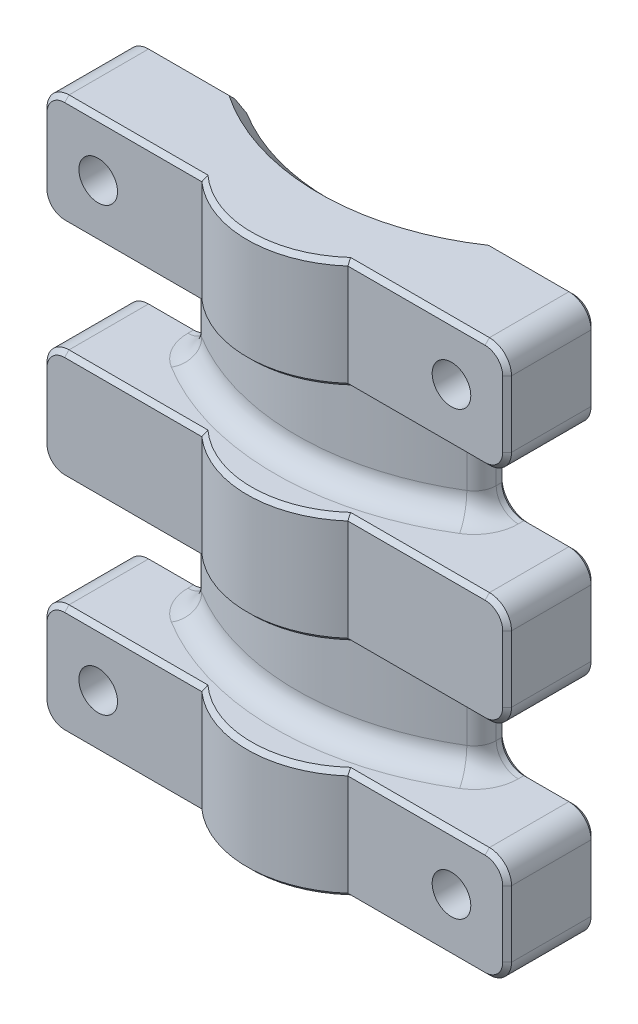
SolidWorks part; units mm, degrees
ref_plane "Front Plane" through (0, 0, 0) normal (0, 0, 1) x (1, 0, 0)
ref_plane "Top Plane" through (0, 0, 0) normal (0, 1, 0) x (1, 0, 0)
ref_plane "Right Plane" through (0, 0, 0) normal (1, 0, 0) x (0, 0, -1)
sketch "Sketch1" plane through (0, 0, 0) normal (0, 1, 0) x (1, 0, 0)
  line L0 (-21.0405, 41) -> (21.0405, 41) construction
  line L1 (-21.0405, 41) -> (21.0405, 41) construction
  line L2 (-21.0405, 26) -> (-6.6144, 26) construction
  line L3 (6.6144, 26) -> (21.0405, 26) construction
  line L4 (-6.6144, 26) -> (0, 26) construction
  line L5 (0, 26) -> (6.6144, 26) construction
  line L6 (0, 28.5) -> (0, 23.5) construction
  line L7 (0, 41) -> (0, 38) construction
  line L8 (-21.0405, 41) -> (-10.5357, 41)
  line L9 (10.5357, 41) -> (21.0405, 41)
  line L10 (-21.0405, 41) -> (-21.0405, 33)
  line L11 (-21.0405, 33) -> (-6.6144, 33)
  line L12 (21.0405, 33) -> (21.0405, 41)
  line L13 (6.6144, 33) -> (21.0405, 33)
  line L14 (0, 35) -> (0, 38) construction
  line L15 (-6.6144, 33) -> (-5.8828, 35.7651) construction
  arc A0 (-21.0405, 26) -> (-21.0405, 41) centre (-2.5, 33.5) cw construction
  arc A1 (21.0405, 41) -> (21.0405, 26) centre (2.5, 33.5) cw construction
  arc A2 (21.0405, 26) -> (21.0405, 41) centre (2.5, 33.5) ccw construction
  arc A3 (-6.6144, 26) -> (6.6144, 26) centre (0, 18.5) cw construction
  arc A4 (-6.6144, 26) -> (6.6144, 26) centre (0, 33.5) ccw construction
  arc A5 (-10.5357, 41) -> (10.5357, 41) centre (0, 58) ccw
  arc A6 (-6.6144, 33) -> (6.6144, 33) centre (0, 40.5) ccw
  arc A7 (-15.4919, 41) -> (15.4919, 41) centre (0, 58) ccw construction
  dimension "D1" = 20
  dimension "D2" = 3
  dimension "D3" = 8
  dimension "D4" = 3
extrude "Boss-Extrude1" add sketch "Sketch1" against normal up to surface (50 mm away) from surface at 25
sketch "Sketch2" plane through (0, 0, -41) normal (0, 0, -1) x (-1, 0, 0)
  line L0 (-16, 20) -> (16, 20) construction
  line L1 (0, 20) -> (0, -20) construction
  line L2 (-16, -20) -> (16, -20) construction
  circle A0 centre (-16, 20) radius 1.75
  circle A1 centre (16, 20) radius 1.75
  circle A2 centre (-16, -20) radius 1.75
  circle A3 centre (16, -20) radius 1.75
  point P15 (0, 0)
  dimension "D1" = 3.5
  dimension "D2" = 40
  dimension "D3" = 32
extrude "Cut-Extrude1" cut sketch "Sketch2" against normal through all
sketch "Sketch3" plane through (0, 0, 0) normal (0, 1, 0) x (1, 0, 0)
  line L1 (-21.0405, 41) -> (-21.0405, 8.3823)
  line L2 (-21.0405, 8.3823) -> (21.0405, 8.3823)
  line L3 (21.0405, 8.3823) -> (21.0405, 41)
  line L5 (0, 0) -> (0, 58) construction
  line L7 (-12.9615, 39) -> (-12.9615, 41)
  line L8 (-21.0405, 41) -> (-10.5357, 41) construction
  line L9 (12.9615, 39) -> (12.9615, 41)
  line L10 (10.5357, 41) -> (21.0405, 41) construction
  line L11 (-12.9615, 41) -> (-21.0405, 41)
  line L12 (12.9615, 41) -> (21.0405, 41)
  line L13 (-21.0405, 41) -> (-21.0405, 33) construction
  arc A0 (-12.9615, 39) -> (12.9615, 39) centre (0, 58) ccw
  arc A1 (-10.5357, 41) -> (10.5357, 41) centre (0, 58) ccw construction
  arc A2 (-15.4919, 41) -> (15.4919, 41) centre (0, 58) ccw construction
  arc A3 (-21.0405, 41) -> (-21.0405, 26) centre (-2.5, 33.5) ccw construction
  point P1 (-21.0405, 41)
  point P29 (21.0997, 40.852)
  dimension "D1" = 2
extrude "Cut-Extrude2" cut sketch "Sketch3" against normal blind 10 from offset 5 offset against normal yes
mirror "Mirror1" about plane through (0, 0, 0) normal (0, 1, 0) of "Cut-Extrude2"
chamfer "Chamfer1" distance 2 angle 45 4 edges at (-17.75, 20, -41) (14.25, 20, -41) (14.25, -20, -41) (-17.75, -20, -41)
chamfer "Chamfer2" distance 1 angle 45 2 edges at (0, -25, -38) (0, 25, -38)
fillet "Fillet1" radius 2 12 edges at (-21.0405, 15, -37) (-21.0405, 5, -37) (-21.0405, -5, -37) (-21.0405, -15, -37) (-21.0405, -25, -37) (21.0405, -25, -37) (21.0405, -15, -37) (21.0405, -5, -37) (21.0405, 5, -37) (21.0405, 15, -37) (21.0405, 25, -37) (-21.0405, 25, -37)
fillet "Fillet3" radius 2 4 edges at (12.9615, 10, -39) (12.9615, -10, -39) (-12.9615, -10, -39) (-12.9615, 10, -39)
chamfer "Chamfer3" [suppressed] distance 1 angle 45
chamfer "Chamfer4" distance 0.4 angle 45 36 edges at (0, -25, -30.5) (-12.8274, -25, -33) (12.8274, -25, -33) (-20.4547, -24.4142, -33) (20.4547, -24.4142, -33) (-21.0405, -20, -33) (21.0405, -20, -33) (-20.4547, -15.5858, -33) (20.4547, -15.5858, -33) (-12.8274, -15, -33) (12.8274, -15, -33) (0, -15, -30.5) (12.8274, 5, -33) (20.4547, 4.4142, -33) (21.0405, 0, -33) (20.4547, -4.4142, -33) (12.8274, -5, -33) (0, -5, -30.5) (-12.8274, -5, -33) (-20.4547, -4.4142, -33) (-21.0405, 0, -33) (-20.4547, 4.4142, -33) (-12.8274, 5, -33) (0, 5, -30.5) (-12.8274, 25, -33) (-20.4547, 24.4142, -33) (-21.0405, 20, -33) (-20.4547, 15.5858, -33) (-12.8274, 15, -33) (0, 15, -30.5) (12.8274, 15, -33) (20.4547, 15.5858, -33) (21.0405, 20, -33) (20.4547, 24.4142, -33) (12.8274, 25, -33) (0, 25, -30.5)
fillet "Fillet2" radius 2 20 edges at (12.9615, -5, -40.5439) (12.7062, -5, -39.11) (-12.9615, -5, -40.5439) (-12.7062, -5, -39.11) (12.9615, 15, -40.5439) (12.7062, 15, -39.11) (-12.9615, 15, -40.5439) (-12.7062, 15, -39.11) (12.9615, -15, -40.5439) (12.7062, -15, -39.11) (-12.9615, -15, -40.5439) (-12.7062, -15, -39.11) (12.9615, 5, -40.5439) (12.7062, 5, -39.11) (-12.9615, 5, -40.5439) (-12.7062, 5, -39.11) (0, -5, -35) (0, 15, -35) (0, -15, -35) (0, 5, -35)
chamfer "Chamfer5" distance 0.4 angle 45 42 edges at (-15.6847, -25, -41) (-20.4547, -24.4142, -41) (-21.0405, -20, -41) (-20.4547, -15.5858, -41) (-17.001, -15, -41) (-13.5473, -14.4142, -41) (-12.9615, -10, -41) (-13.5473, -5.5858, -41) (-17.001, -5, -41) (-20.4547, -4.4142, -41) (-21.0405, 0, -41) (-20.4547, 4.4142, -41) (-17.001, 5, -41) (-13.5473, 5.5858, -41) (-12.9615, 10, -41) (-13.5473, 14.4142, -41) (-17.001, 15, -41) (-20.4547, 15.5858, -41) (-21.0405, 20, -41) (-20.4547, 24.4142, -41) (-15.6847, 25, -41) (15.6847, -25, -41) (20.4547, -24.4142, -41) (21.0405, -20, -41) (20.4547, -15.5858, -41) (17.001, -15, -41) (13.5473, -14.4142, -41) (12.9615, -10, -41) (13.5473, -5.5858, -41) (17.001, -5, -41) (20.4547, -4.4142, -41) (21.0405, 0, -41) (20.4547, 4.4142, -41) (17.001, 5, -41) (13.5473, 5.5858, -41) (12.9615, 10, -41) (13.5473, 14.4142, -41) (17.001, 15, -41) (20.4547, 15.5858, -41) (21.0405, 20, -41) (20.4547, 24.4142, -41) (15.6847, 25, -41)
